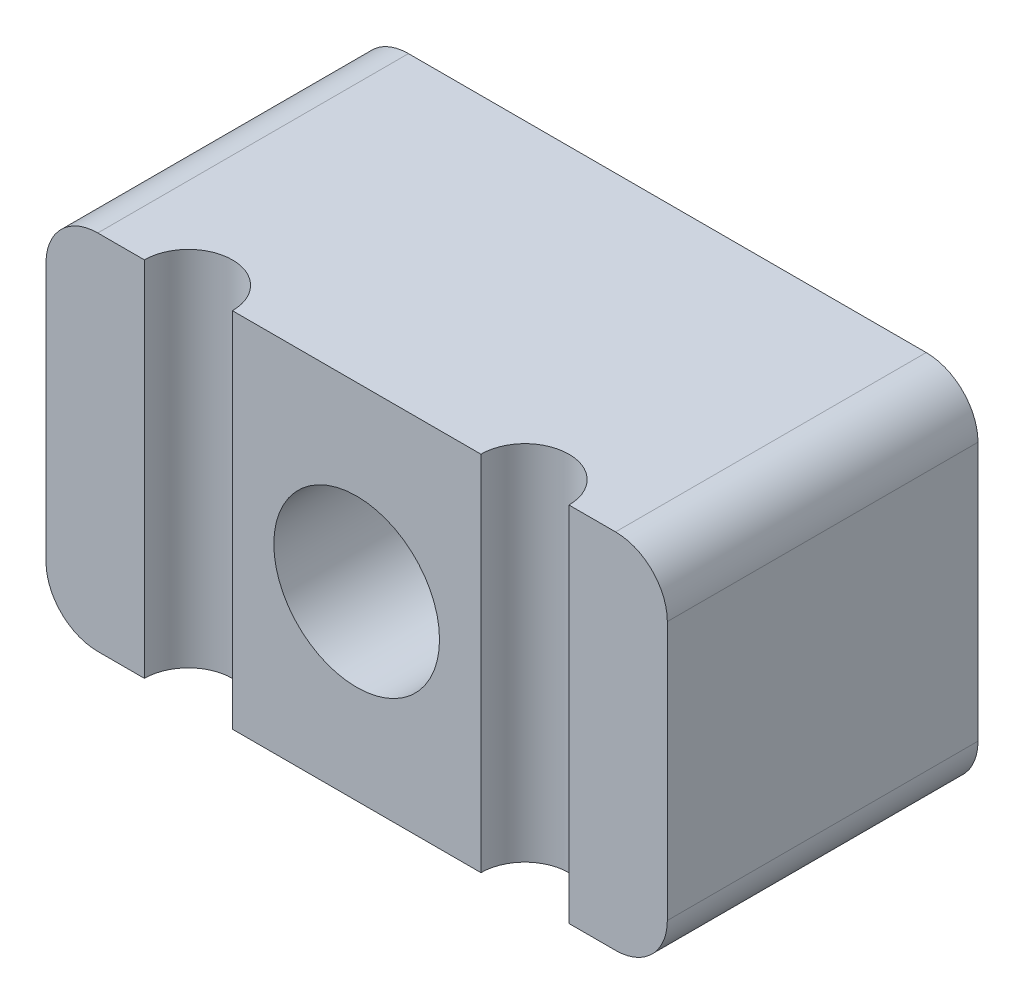
SolidWorks part; units mm, degrees
ref_plane "Front Plane" through (0, 0, 0) normal (0, 0, 1) x (1, 0, 0)
ref_plane "Top Plane" through (0, 0, 0) normal (0, 1, 0) x (1, 0, 0)
ref_plane "Right Plane" through (0, 0, 0) normal (1, 0, 0) x (0, 0, -1)
sketch "Sketch1" plane through (0, 0, 0) normal (0, 0, 1) x (1, 0, 0)
  line L0 (12, 6) -> (12, 1)
  line L1 (11, 7) -> (1, 7)
  line L2 (0, 6) -> (0, 1)
  line L3 (11, 0) -> (1, 0)
  arc A0 (0, 1) -> (1, 0) centre (1, 1) ccw
  arc A1 (1, 7) -> (0, 6) centre (1, 6) ccw
  arc A2 (12, 6) -> (11, 7) centre (11, 6) ccw
  arc A3 (12, 1) -> (11, 0) centre (11, 1) cw
  circle A4 centre (6, 3.5) radius 1.6
extrude "Boss-Extrude1" add sketch "Sketch1" along normal blind 6
sketch "Sketch2" plane through (0, 0, 0) normal (0, -1, 0) x (1, 0, 0)
  line L2 (1.9, 6) -> (3.6, 6)
  line L3 (8.4, 6) -> (10.1, 6)
  arc A2 (8.4, 6) -> (10.1, 6) centre (9.25, 6) ccw
  arc A3 (1.9, 6) -> (3.6, 6) centre (2.75, 6) ccw
extrude "Cut-Extrude1" cut sketch "Sketch2" against normal up to surface (7 mm away) up to face at (6, 7, 3)
